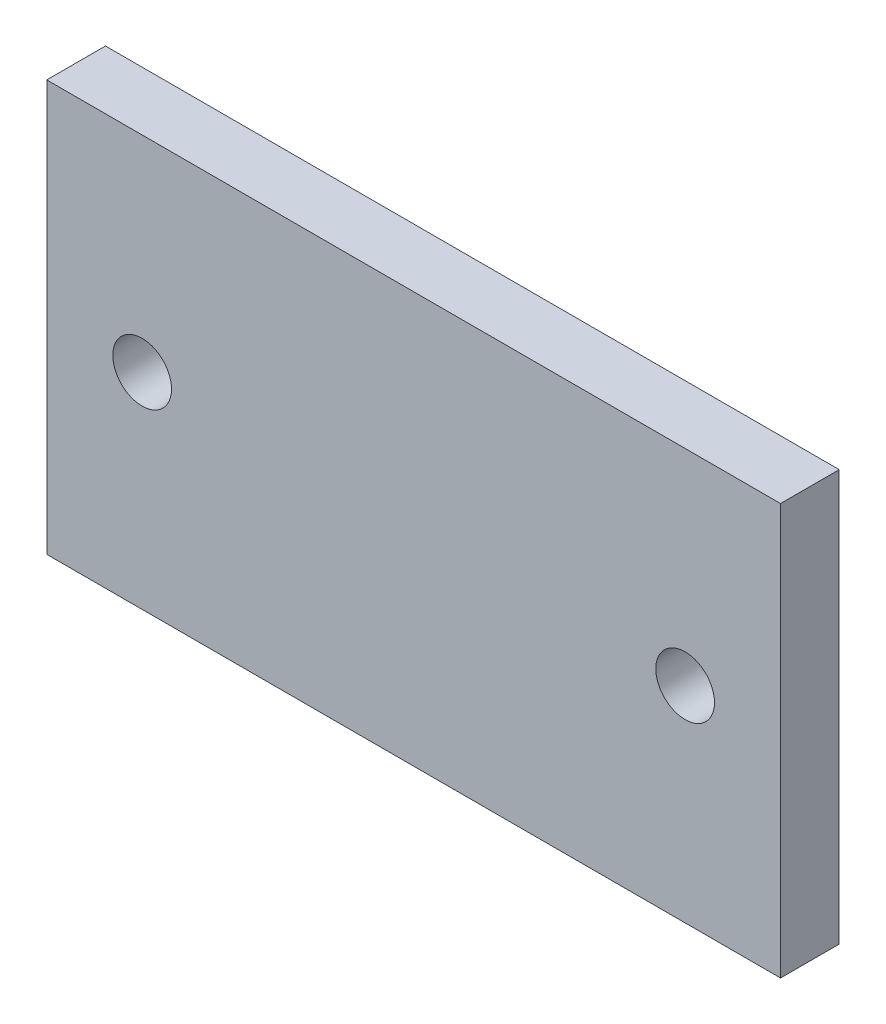
SolidWorks part; units mm, degrees
material "ASTM A36 Steel"
ref_plane "Front Plane" through (0, 0, 0) normal (0, 0, 1) x (1, 0, 0)
ref_plane "Top Plane" through (0, 0, 0) normal (0, 1, 0) x (1, 0, 0)
ref_plane "Right Plane" through (0, 0, 0) normal (1, 0, 0) x (0, 0, -1)
sketch "Sketch1" plane through (0, 0, 0) normal (0, 0, 1) x (1, 0, 0)
  line L1 (107.467, 43.9356) -> (-142.533, 43.9356)
  line L2 (107.467, 43.9356) -> (107.467, -96.0644)
  line L3 (107.467, -96.0644) -> (-142.533, -96.0644)
  line L4 (-142.533, 43.9356) -> (-142.533, -96.0644)
  circle A0 centre (74.967, -26.0644) radius 10
  circle A1 centre (-110.033, -26.0644) radius 10
  dimension "D3" = 20
  dimension "D4" = 20
  dimension "D6" = 185
  dimension "D1" = 250
  dimension "D2" = 140
  dimension "D5" = 32.5
extrude "Boss-Extrude1" add sketch "Sketch1" along normal blind 20
